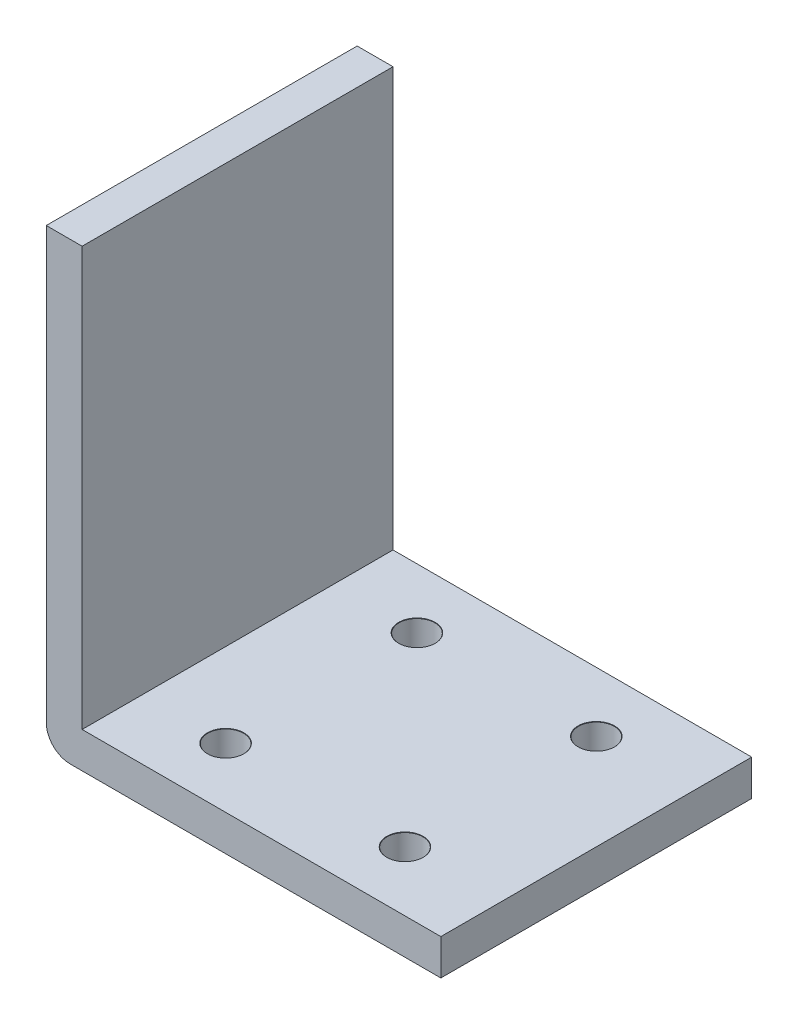
SolidWorks part; units mm, degrees
ref_plane "Front Plane" through (0, 0, 0) normal (0, 0, 1) x (1, 0, 0)
ref_plane "Top Plane" through (0, 0, 0) normal (0, 1, 0) x (1, 0, 0)
ref_plane "Right Plane" through (0, 0, 0) normal (1, 0, 0) x (0, 0, -1)
sketch "Sketch1" plane through (0, 0, 0) normal (0, 1, 0) x (1, 0, 0)
  line L1 (0, 0) -> (33, 0)
  line L2 (0, 0) -> (0, 26)
  line L3 (0, 26) -> (33, 26)
  line L4 (33, 0) -> (33, 26)
  dimension "D1" = 26
  dimension "D2" = 33
extrude "Boss-Extrude1" add sketch "Sketch1" along normal blind 3
sketch "Sketch2" plane through (0, 3, 0) normal (0, 1, 0) x (1, 0, 0)
  line L0 (0, 0) -> (33, 0) construction
  line L1 (0, 26) -> (3, 26)
  line L2 (0, 26) -> (0, 0)
  line L3 (0, 0) -> (3, 0)
  line L4 (3, 26) -> (3, 0)
  dimension "D1" = 3
extrude "Boss-Extrude2" add sketch "Sketch2" along normal blind 35
fillet "Fillet1" radius 2 1 edges at (0, 0, -13)
sketch "Sketch3" plane through (0, 3, 0) normal (0, 1, 0) x (1, 0, 0)
  line L0 (33, 26) -> (3, 26) construction
  line L1 (10, 21) -> (25, 21)
  line L2 (10, 21) -> (10, 5)
  line L3 (10, 5) -> (25, 5)
  line L4 (25, 21) -> (25, 5)
  line L5 (10, 21) -> (25, 5) construction
  line L6 (10, 5) -> (25, 21) construction
  line L7 (3, 0) -> (33, 0) construction
  line L9 (33, 0) -> (33, 26) construction
  point P0 (17.5, 13)
  dimension "D1" = 15
  dimension "D2" = 16
  dimension "D3" = 5
  dimension "D4" = 5
  dimension "D5" = 8
hole_wizard "Ø3.0mm Dowel Hole1" positions "Sketch4" profile "Sketch5" hole size "Ø3.0" standard "ISO" end condition through all
sketch "Sketch4" plane through (0, 3, 0) normal (0, 1, 0) x (1, 0, 0)
  point P0 (25, 21)
  point P3 (10, 21)
  point P6 (25, 5)
  point P9 (10, 5)
sketch "Sketch5" plane through (25, 3, -21) normal (1, 0, 0) x (0, 0, 1)
  line L0 (0, 0) -> (0, 3)
  line L1 (0, 3) -> (1.5, 3)
  line L2 (1.5, 3) -> (1.5, 0.025)
  line L3 (1.5, 0.025) -> (1.525, 0)
  line L5 (1.525, 0) -> (0, 0)
  line L6 (-1.5, 0.025) -> (-1.525, 0) construction
  line L11 (0, -6.35) -> (0, 107.95) construction
  dimension "Thru Hole Dia." = 3
  dimension "Thru Hole Depth" = 3
  dimension "Near C'Sink Dia." = 3.05
  dimension "Near C'Sink Angle" = 90
sketch "Sketch6" plane through (0, 0, 0) normal (-1, 0, 0) x (0, 0, 1)
  line L0 (-26, 38) -> (0, 2) construction
  line L1 (0, 2) -> (0, 38) construction
  line L2 (0, 38) -> (-26, 2) construction
